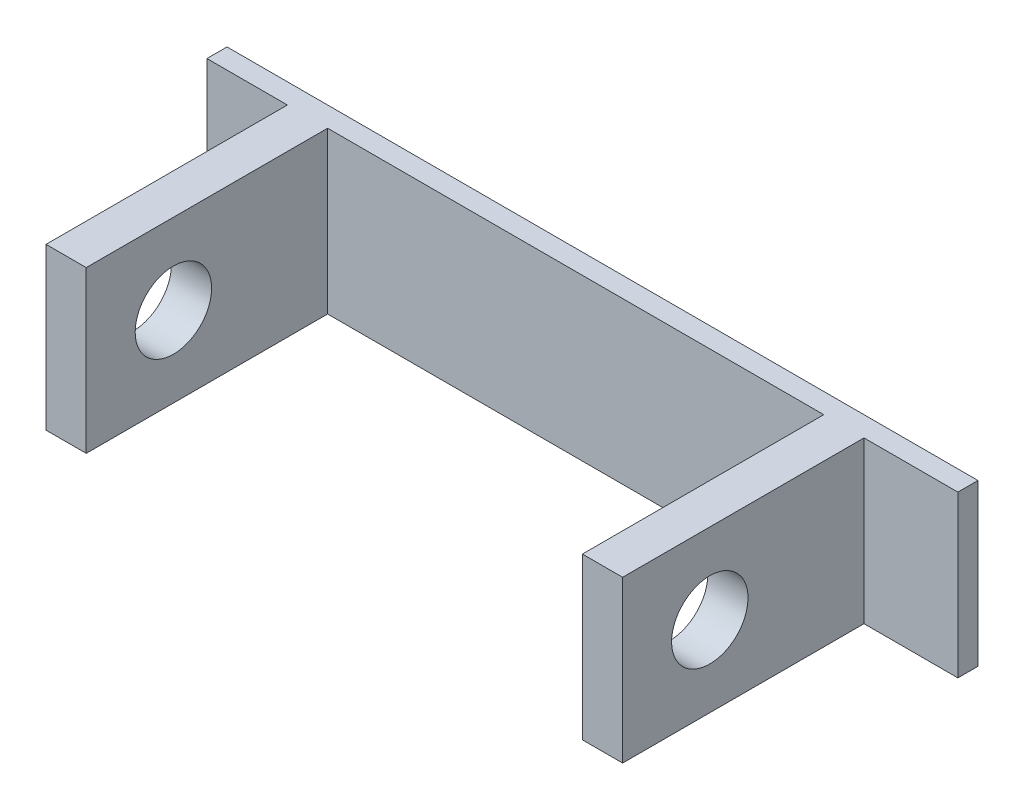
SolidWorks part; units mm, degrees
ref_plane "前视基准面" through (0, 0, 0) normal (0, 0, 1) x (1, 0, 0)
ref_plane "上视基准面" through (0, 0, 0) normal (0, 1, 0) x (1, 0, 0)
ref_plane "右视基准面" through (0, 0, 0) normal (1, 0, 0) x (0, 0, -1)
sketch "草图2" plane through (0, 0, 0) normal (0, 0, 1) x (1, 0, 0)
  line L1 (-28, 6) -> (28, 6)
  line L2 (-28, 6) -> (-28, -6)
  line L3 (-28, -6) -> (28, -6)
  line L4 (28, 6) -> (28, -6)
  line L5 (-28, 6) -> (28, -6) construction
  line L6 (-28, -6) -> (28, 6) construction
  point P0 (0, 0)
  dimension "D1" = 12
  dimension "D2" = 56
extrude "凸台-拉伸1" add sketch "草图2" along normal blind 1.5
sketch "草图3" plane through (0, 0, 1.5) normal (0, 0, 1) x (1, 0, 0)
  line L0 (28, 6) -> (-28, 6) construction
  line L1 (-22, 6) -> (-19, 6)
  line L2 (-22, 6) -> (-22, -6)
  line L3 (-22, -6) -> (-19, -6)
  line L4 (-19, 6) -> (-19, -6)
  line L5 (-28, -6) -> (28, -6) construction
  line L6 (-28, 6) -> (-28, -6) construction
  line L7 (18, 6) -> (21, 6)
  line L8 (18, 6) -> (18, -6)
  line L9 (18, -6) -> (21, -6)
  line L10 (21, 6) -> (21, -6)
  line L11 (28, -6) -> (28, 6) construction
  dimension "D1" = 3
  dimension "D2" = 3
  dimension "D3" = 6
  dimension "D4" = 7
extrude "凸台-拉伸2" add sketch "草图3" along normal blind 18
sketch "草图4" plane through (21, 0, 0) normal (1, 0, 0) x (0, 0, -1)
  line L0 (-1.5, -6) -> (-1.5, 6) construction
  circle A0 centre (-13, 0) radius 2.85
  dimension "D1" = 5.7
  dimension "D2" = 11.5
extrude "切除-拉伸1" cut sketch "草图4" against normal through all
